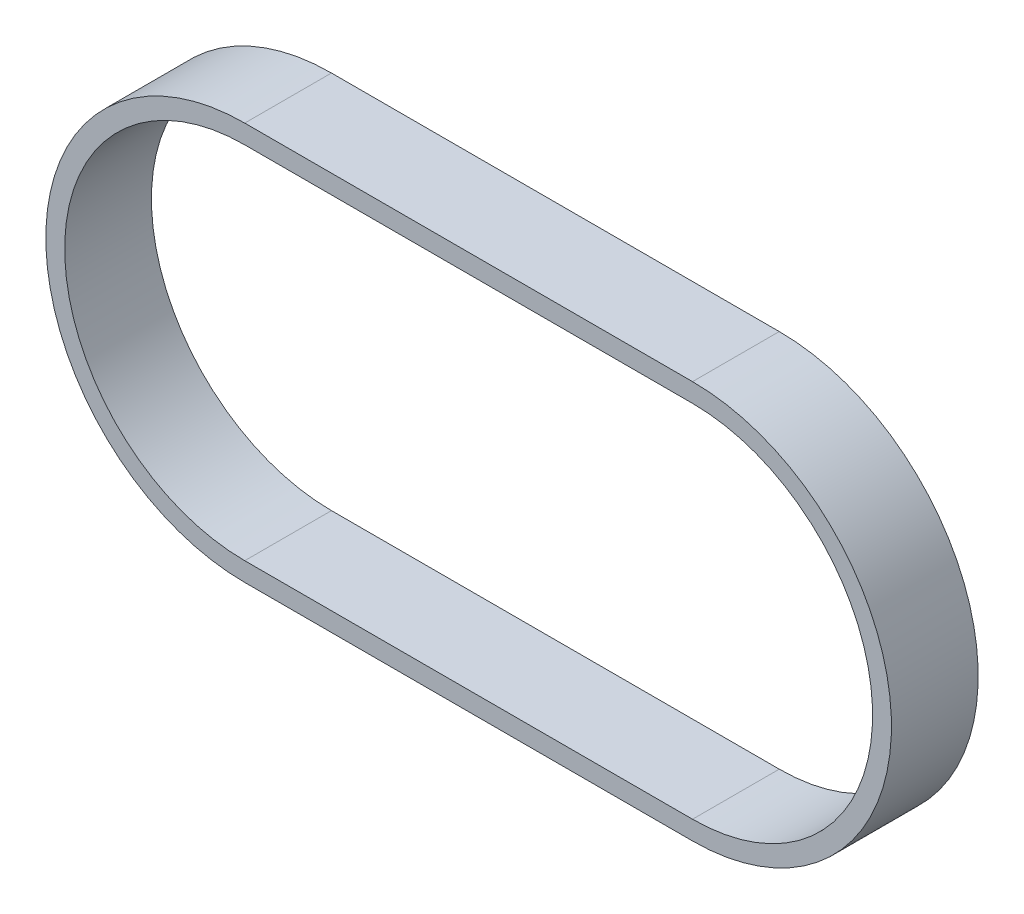
SolidWorks part; units mm, degrees
ref_plane "Front Plane" through (0, 0, 0) normal (0, 0, 1) x (1, 0, 0)
ref_plane "Top Plane" through (0, 0, 0) normal (0, 1, 0) x (1, 0, 0)
ref_plane "Right Plane" through (0, 0, 0) normal (1, 0, 0) x (0, 0, -1)
sketch "Sketch1" plane through (0, 0, 0) normal (0, 0, 1) x (1, 0, 0)
  line L0 (0, 0) -> (47.5, 0) construction
  line L1 (0, 19.1) -> (47.5, 19.1)
  line L2 (0, -19.1) -> (47.5, -19.1)
  circle A0 centre (0, 0) radius 19.1 construction
  circle A1 centre (47.5, 0) radius 19.1 construction
  arc A2 (47.5, -19.1) -> (47.5, 19.1) centre (47.5, 0) ccw
  arc A3 (0, 19.1) -> (0, -19.1) centre (0, 0) ccw
  dimension "D2" = 38.2
  dimension "D1" = 47.5
extrude "Extrude-Thin1" add sketch "Sketch1" along normal blind 9.2 thin thin type one direction wall 2
equation "\"pitchDiameter\"= 38.2mm"
equation "\"pulley2pulleyDistance\" = 47.5mm"
equation "\"D1@Sketch1\"=\"pulley2pulleyDistance\""
equation "\"D2@Sketch1\"=\"pitchDiameter\""
